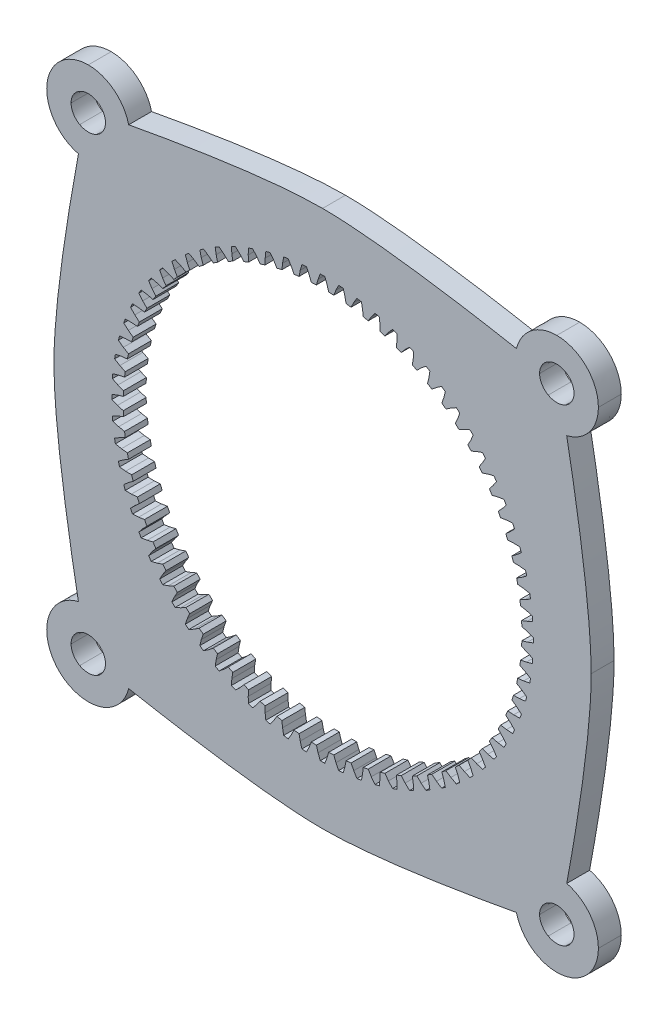
SolidWorks part; units mm, degrees
ref_plane "Front Plane" through (0, 0, 0) normal (0, 0, 1) x (1, 0, 0)
ref_plane "Top Plane" through (0, 0, 0) normal (0, 1, 0) x (1, 0, 0)
ref_plane "Right Plane" through (0, 0, 0) normal (1, 0, 0) x (0, 0, -1)
sketch "ring" plane through (10.9807, 0, 0) normal (0, 0, 1) x (1, 0, 0)
  line L432 (61.0696, 218.6762) -> (61.8666, 218.4468)
  line L433 (61.8666, 218.4468) -> (62.6621, 218.14)
  line L434 (62.6621, 218.14) -> (62.6621, 217.5117)
  line L435 (62.6621, 217.5117) -> (61.8666, 217.205)
  line L436 (61.8666, 217.205) -> (61.0696, 216.9755)
  line L437 (61.0696, 216.9755) -> (61.0385, 216.2626)
  line L438 (61.0385, 216.2626) -> (61.8124, 215.9646)
  line L439 (61.8124, 215.9646) -> (62.578, 215.5895)
  line L440 (62.578, 215.5895) -> (62.5233, 214.9638)
  line L441 (62.5233, 214.9638) -> (61.704, 214.7276)
  line L442 (61.704, 214.7276) -> (60.8904, 214.5682)
  line L443 (60.8904, 214.5682) -> (60.7972, 213.8609)
  line L444 (60.7972, 213.8609) -> (61.542, 213.4966)
  line L445 (61.542, 213.4966) -> (62.2721, 213.0563)
  line L446 (62.2721, 213.0563) -> (62.1632, 212.4377)
  line L447 (62.1632, 212.4377) -> (61.3264, 212.2737)
  line L448 (61.3264, 212.2737) -> (60.5017, 212.1859)
  line L449 (60.5017, 212.1859) -> (60.3474, 211.4894)
  line L450 (60.3474, 211.4894) -> (61.0577, 211.0616)
  line L451 (61.0577, 211.0616) -> (61.7466, 210.5592)
  line L452 (61.7466, 210.5592) -> (61.5841, 209.9524)
  line L453 (61.5841, 209.9524) -> (60.7363, 209.8621)
  line L454 (60.7363, 209.8621) -> (59.9071, 209.8466)
  line L455 (59.9071, 209.8466) -> (59.6926, 209.1662)
  line L456 (59.6926, 209.1662) -> (60.3629, 208.6779)
  line L457 (60.3629, 208.6779) -> (61.0055, 208.1174)
  line L458 (61.0055, 208.1174) -> (60.7907, 207.5273)
  line L459 (60.7907, 207.5273) -> (59.9381, 207.5112)
  line L460 (59.9381, 207.5112) -> (59.1109, 207.5679)
  line L461 (59.1109, 207.5679) -> (58.8378, 206.9087)
  line L462 (58.8378, 206.9087) -> (59.4632, 206.364)
  line L463 (59.4632, 206.364) -> (60.0544, 205.7496)
  line L464 (60.0544, 205.7496) -> (59.7891, 205.1803)
  line L465 (59.7891, 205.1803) -> (58.9382, 205.2385)
  line L466 (58.9382, 205.2385) -> (58.1189, 205.3672)
  line L467 (58.1189, 205.3672) -> (57.7896, 204.7344)
  line L468 (57.7896, 204.7344) -> (58.365, 204.1372)
  line L469 (58.365, 204.1372) -> (58.9007, 203.4737)
  line L470 (58.9007, 203.4737) -> (58.5866, 202.9299)
  line L471 (58.5866, 202.9299) -> (57.7441, 203.062)
  line L472 (57.7441, 203.062) -> (56.9392, 203.2615)
  line L473 (56.9392, 203.2615) -> (56.556, 202.6598)
  line L474 (56.556, 202.6598) -> (57.077, 202.0146)
  line L475 (57.077, 202.0146) -> (57.5528, 201.3068)
  line L476 (57.5528, 201.3068) -> (57.1924, 200.7926)
  line L477 (57.1924, 200.7926) -> (56.3646, 200.9975)
  line L478 (56.3646, 200.9975) -> (55.5803, 201.2665)
  line L479 (55.5803, 201.2665) -> (55.146, 200.7006)
  line L480 (55.146, 200.7006) -> (55.6089, 200.0126)
  line L481 (55.6089, 200.0126) -> (56.0212, 199.2661)
  line L482 (56.0212, 199.2661) -> (55.6173, 198.7849)
  line L483 (55.6173, 198.7849) -> (54.8107, 199.0612)
  line L484 (54.8107, 199.0612) -> (54.0527, 199.3976)
  line L485 (54.0527, 199.3976) -> (53.5706, 198.8715)
  line L486 (53.5706, 198.8715) -> (53.972, 198.1457)
  line L487 (53.972, 198.1457) -> (54.3174, 197.3662)
  line L488 (54.3174, 197.3662) -> (53.8735, 196.9222)
  line L489 (53.8735, 196.9222) -> (53.094, 197.2677)
  line L490 (53.094, 197.2677) -> (52.3681, 197.669)
  line L491 (52.3681, 197.669) -> (51.842, 197.187)
  line L492 (51.842, 197.187) -> (52.1784, 196.4289)
  line L493 (52.1784, 196.4289) -> (52.4547, 195.6223)
  line L494 (52.4547, 195.6223) -> (51.9735, 195.2185)
  line L495 (51.9735, 195.2185) -> (51.2271, 195.6308)
  line L496 (51.2271, 195.6308) -> (50.539, 196.0936)
  line L497 (50.539, 196.0936) -> (49.9732, 195.6593)
  line L498 (49.9732, 195.6593) -> (50.2421, 194.875)
  line L499 (50.2421, 194.875) -> (50.447, 194.0472)
  line L500 (50.447, 194.0472) -> (49.9328, 193.6868)
  line L501 (49.9328, 193.6868) -> (49.225, 194.1627)
  line L502 (49.225, 194.1627) -> (48.5798, 194.6836)
  line L503 (48.5798, 194.6836) -> (47.9781, 194.3004)
  line L504 (47.9781, 194.3004) -> (48.1777, 193.4955)
  line L505 (48.1777, 193.4955) -> (48.3097, 192.6531)
  line L506 (48.3097, 192.6531) -> (47.7659, 192.3389)
  line L507 (47.7659, 192.3389) -> (47.1024, 192.8746)
  line L508 (47.1024, 192.8746) -> (46.5052, 193.45)
  line L509 (46.5052, 193.45) -> (45.8725, 193.1207)
  line L510 (45.8725, 193.1207) -> (46.0012, 192.3014)
  line L511 (46.0012, 192.3014) -> (46.0593, 191.4505)
  line L512 (46.0593, 191.4505) -> (45.4901, 191.1852)
  line L513 (45.4901, 191.1852) -> (44.8757, 191.7765)
  line L514 (44.8757, 191.7765) -> (44.331, 192.4019)
  line L515 (44.331, 192.4019) -> (43.6717, 192.1287)
  line L516 (43.6717, 192.1287) -> (43.7284, 191.3015)
  line L517 (43.7284, 191.3015) -> (43.7123, 190.4489)
  line L518 (43.7123, 190.4489) -> (43.1222, 190.2341)
  line L519 (43.1222, 190.2341) -> (42.5617, 190.8767)
  line L520 (42.5617, 190.8767) -> (42.0735, 191.547)
  line L521 (42.0735, 191.547) -> (41.393, 191.3325)
  line L522 (41.393, 191.3325) -> (41.3775, 190.5034)
  line L523 (41.3775, 190.5034) -> (41.2872, 189.6556)
  line L524 (41.2872, 189.6556) -> (40.6804, 189.493)
  line L525 (40.6804, 189.493) -> (40.1781, 190.1819)
  line L526 (40.1781, 190.1819) -> (39.7502, 190.8923)
  line L527 (39.7502, 190.8923) -> (39.0537, 190.7379)
  line L528 (39.0537, 190.7379) -> (38.9659, 189.9132)
  line L529 (38.9659, 189.9132) -> (38.802, 189.0764)
  line L530 (38.802, 189.0764) -> (38.1833, 188.9675)
  line L531 (38.1833, 188.9675) -> (37.7431, 189.6976)
  line L532 (37.7431, 189.6976) -> (37.3787, 190.4424)
  line L533 (37.3787, 190.4424) -> (36.6715, 190.3493)
  line L534 (36.6715, 190.3493) -> (36.512, 189.5356)
  line L535 (36.512, 189.5356) -> (36.2758, 188.7163)
  line L536 (36.2758, 188.7163) -> (35.6501, 188.6616)
  line L537 (35.6501, 188.6616) -> (35.275, 189.4273)
  line L538 (35.275, 189.4273) -> (34.977, 190.2011)
  line L539 (34.977, 190.2011) -> (34.2641, 190.1701)
  line L540 (34.2641, 190.1701) -> (34.0347, 189.3731)
  line L541 (34.0347, 189.3731) -> (33.7279, 188.5775)
  line L542 (33.7279, 188.5775) -> (33.0997, 188.5775)
  line L543 (33.0997, 188.5775) -> (32.7929, 189.3731)
  line L544 (32.7929, 189.3731) -> (32.5634, 190.1701)
  line L545 (32.5634, 190.1701) -> (31.8505, 190.2011)
  line L546 (31.8505, 190.2011) -> (31.5525, 189.4273)
  line L547 (31.5525, 189.4273) -> (31.1774, 188.6616)
  line L548 (31.1774, 188.6616) -> (30.5518, 188.7163)
  line L549 (30.5518, 188.7163) -> (30.3155, 189.5356)
  line L550 (30.3155, 189.5356) -> (30.1561, 190.3493)
  line L551 (30.1561, 190.3493) -> (29.4488, 190.4424)
  line L552 (29.4488, 190.4424) -> (29.0845, 189.6976)
  line L553 (29.0845, 189.6976) -> (28.6442, 188.9675)
  line L554 (28.6442, 188.9675) -> (28.0256, 189.0764)
  line L555 (28.0256, 189.0764) -> (27.8616, 189.9132)
  line L556 (27.8616, 189.9132) -> (27.7738, 190.7379)
  line L557 (27.7738, 190.7379) -> (27.0773, 190.8923)
  line L558 (27.0773, 190.8923) -> (26.6495, 190.1819)
  line L559 (26.6495, 190.1819) -> (26.1471, 189.493)
  line L560 (26.1471, 189.493) -> (25.5403, 189.6556)
  line L561 (25.5403, 189.6556) -> (25.45, 190.5034)
  line L562 (25.45, 190.5034) -> (25.4345, 191.3325)
  line L563 (25.4345, 191.3325) -> (24.7541, 191.547)
  line L564 (24.7541, 191.547) -> (24.2658, 190.8767)
  line L565 (24.2658, 190.8767) -> (23.7053, 190.2341)
  line L566 (23.7053, 190.2341) -> (23.1152, 190.4489)
  line L567 (23.1152, 190.4489) -> (23.0991, 191.3015)
  line L568 (23.0991, 191.3015) -> (23.1558, 192.1287)
  line L569 (23.1558, 192.1287) -> (22.4966, 192.4019)
  line L570 (22.4966, 192.4019) -> (21.9519, 191.7765)
  line L571 (21.9519, 191.7765) -> (21.3375, 191.1852)
  line L572 (21.3375, 191.1852) -> (20.7682, 191.4505)
  line L573 (20.7682, 191.4505) -> (20.8264, 192.3014)
  line L574 (20.8264, 192.3014) -> (20.9551, 193.1207)
  line L575 (20.9551, 193.1207) -> (20.3223, 193.45)
  line L576 (20.3223, 193.45) -> (19.7251, 192.8746)
  line L577 (19.7251, 192.8746) -> (19.0616, 192.3389)
  line L578 (19.0616, 192.3389) -> (18.5178, 192.6531)
  line L579 (18.5178, 192.6531) -> (18.6499, 193.4955)
  line L580 (18.6499, 193.4955) -> (18.8494, 194.3004)
  line L581 (18.8494, 194.3004) -> (18.2477, 194.6836)
  line L582 (18.2477, 194.6836) -> (17.6025, 194.1627)
  line L583 (17.6025, 194.1627) -> (16.8947, 193.6868)
  line L584 (16.8947, 193.6868) -> (16.3805, 194.0472)
  line L585 (16.3805, 194.0472) -> (16.5854, 194.875)
  line L586 (16.5854, 194.875) -> (16.8544, 195.6593)
  line L587 (16.8544, 195.6593) -> (16.2885, 196.0936)
  line L588 (16.2885, 196.0936) -> (15.6005, 195.6308)
  line L589 (15.6005, 195.6308) -> (14.854, 195.2185)
  line L590 (14.854, 195.2185) -> (14.3728, 195.6223)
  line L591 (14.3728, 195.6223) -> (14.6491, 196.4289)
  line L592 (14.6491, 196.4289) -> (14.9855, 197.187)
  line L593 (14.9855, 197.187) -> (14.4594, 197.669)
  line L594 (14.4594, 197.669) -> (13.7336, 197.2677)
  line L595 (13.7336, 197.2677) -> (12.9541, 196.9222)
  line L596 (12.9541, 196.9222) -> (12.5101, 197.3662)
  line L597 (12.5101, 197.3662) -> (12.8556, 198.1457)
  line L598 (12.8556, 198.1457) -> (13.2569, 198.8715)
  line L599 (13.2569, 198.8715) -> (12.7749, 199.3976)
  line L600 (12.7749, 199.3976) -> (12.0168, 199.0612)
  line L601 (12.0168, 199.0612) -> (11.2102, 198.7849)
  line L602 (11.2102, 198.7849) -> (10.8064, 199.2661)
  line L603 (10.8064, 199.2661) -> (11.2187, 200.0126)
  line L604 (11.2187, 200.0126) -> (11.6815, 200.7006)
  line L605 (11.6815, 200.7006) -> (11.2472, 201.2665)
  line L606 (11.2472, 201.2665) -> (10.4629, 200.9975)
  line L607 (10.4629, 200.9975) -> (9.6351, 200.7926)
  line L608 (9.6351, 200.7926) -> (9.2747, 201.3068)
  line L609 (9.2747, 201.3068) -> (9.7506, 202.0146)
  line L610 (9.7506, 202.0146) -> (10.2715, 202.6598)
  line L611 (10.2715, 202.6598) -> (9.8883, 203.2615)
  line L612 (9.8883, 203.2615) -> (9.0834, 203.062)
  line L613 (9.0834, 203.062) -> (8.241, 202.9299)
  line L614 (8.241, 202.9299) -> (7.9268, 203.4737)
  line L615 (7.9268, 203.4737) -> (8.4625, 204.1372)
  line L616 (8.4625, 204.1372) -> (9.038, 204.7344)
  line L617 (9.038, 204.7344) -> (8.7086, 205.3672)
  line L618 (8.7086, 205.3672) -> (7.8893, 205.2385)
  line L619 (7.8893, 205.2385) -> (7.0384, 205.1803)
  line L620 (7.0384, 205.1803) -> (6.7731, 205.7496)
  line L621 (6.7731, 205.7496) -> (7.3644, 206.364)
  line L622 (7.3644, 206.364) -> (7.9898, 206.9087)
  line L623 (7.9898, 206.9087) -> (7.7166, 207.5679)
  line L624 (7.7166, 207.5679) -> (6.8894, 207.5112)
  line L625 (6.8894, 207.5112) -> (6.0368, 207.5273)
  line L626 (6.0368, 207.5273) -> (5.822, 208.1174)
  line L627 (5.822, 208.1174) -> (6.4646, 208.6779)
  line L628 (6.4646, 208.6779) -> (7.1349, 209.1662)
  line L629 (7.1349, 209.1662) -> (6.9204, 209.8466)
  line L630 (6.9204, 209.8466) -> (6.0913, 209.8621)
  line L631 (6.0913, 209.8621) -> (5.2435, 209.9524)
  line L632 (5.2435, 209.9524) -> (5.0809, 210.5592)
  line L633 (5.0809, 210.5592) -> (5.7698, 211.0616)
  line L634 (5.7698, 211.0616) -> (6.4802, 211.4894)
  line L635 (6.4802, 211.4894) -> (6.3258, 212.1859)
  line L636 (6.3258, 212.1859) -> (5.5011, 212.2737)
  line L637 (5.5011, 212.2737) -> (4.6644, 212.4377)
  line L638 (4.6644, 212.4377) -> (4.5554, 213.0563)
  line L639 (4.5554, 213.0563) -> (5.2855, 213.4966)
  line L640 (5.2855, 213.4966) -> (6.0303, 213.8609)
  line L641 (6.0303, 213.8609) -> (5.9372, 214.5682)
  line L642 (5.9372, 214.5682) -> (5.1235, 214.7276)
  line L643 (5.1235, 214.7276) -> (4.3042, 214.9638)
  line L644 (4.3042, 214.9638) -> (4.2495, 215.5895)
  line L645 (4.2495, 215.5895) -> (5.0152, 215.9646)
  line L646 (5.0152, 215.9646) -> (5.789, 216.2626)
  line L647 (5.789, 216.2626) -> (5.758, 216.9755)
  line L648 (5.758, 216.9755) -> (4.961, 217.205)
  line L649 (4.961, 217.205) -> (4.1654, 217.5117)
  line L650 (4.1654, 217.5117) -> (4.1654, 218.14)
  line L651 (4.1654, 218.14) -> (4.961, 218.4468)
  line L652 (4.961, 218.4468) -> (5.758, 218.6762)
  line L653 (5.758, 218.6762) -> (5.789, 219.3891)
  line L654 (5.789, 219.3891) -> (5.0152, 219.6871)
  line L655 (5.0152, 219.6871) -> (4.2495, 220.0622)
  line L656 (4.2495, 220.0622) -> (4.3042, 220.6879)
  line L657 (4.3042, 220.6879) -> (5.1235, 220.9241)
  line L658 (5.1235, 220.9241) -> (5.9372, 221.0836)
  line L659 (5.9372, 221.0836) -> (6.0303, 221.7908)
  line L660 (6.0303, 221.7908) -> (5.2855, 222.1552)
  line L661 (5.2855, 222.1552) -> (4.5554, 222.5954)
  line L662 (4.5554, 222.5954) -> (4.6644, 223.214)
  line L663 (4.6644, 223.214) -> (5.5011, 223.378)
  line L664 (5.5011, 223.378) -> (6.3258, 223.4658)
  line L665 (6.3258, 223.4658) -> (6.4802, 224.1623)
  line L666 (6.4802, 224.1623) -> (5.7698, 224.5902)
  line L667 (5.7698, 224.5902) -> (5.0809, 225.0925)
  line L668 (5.0809, 225.0925) -> (5.2435, 225.6993)
  line L669 (5.2435, 225.6993) -> (6.0913, 225.7896)
  line L670 (6.0913, 225.7896) -> (6.9204, 225.8051)
  line L671 (6.9204, 225.8051) -> (7.1349, 226.4856)
  line L672 (7.1349, 226.4856) -> (6.4646, 226.9738)
  line L673 (6.4646, 226.9738) -> (5.822, 227.5343)
  line L674 (5.822, 227.5343) -> (6.0368, 228.1244)
  line L675 (6.0368, 228.1244) -> (6.8894, 228.1405)
  line L676 (6.8894, 228.1405) -> (7.7166, 228.0838)
  line L677 (7.7166, 228.0838) -> (7.9898, 228.7431)
  line L678 (7.9898, 228.7431) -> (7.3644, 229.2878)
  line L679 (7.3644, 229.2878) -> (6.7731, 229.9022)
  line L680 (6.7731, 229.9022) -> (7.0384, 230.4714)
  line L681 (7.0384, 230.4714) -> (7.8893, 230.4133)
  line L682 (7.8893, 230.4133) -> (8.7086, 230.2846)
  line L683 (8.7086, 230.2846) -> (9.038, 230.9173)
  line L684 (9.038, 230.9173) -> (8.4625, 231.5145)
  line L685 (8.4625, 231.5145) -> (7.9268, 232.178)
  line L686 (7.9268, 232.178) -> (8.241, 232.7218)
  line L687 (8.241, 232.7218) -> (9.0834, 232.5898)
  line L688 (9.0834, 232.5898) -> (9.8883, 232.3902)
  line L689 (9.8883, 232.3902) -> (10.2715, 232.9919)
  line L690 (10.2715, 232.9919) -> (9.7506, 233.6371)
  line L691 (9.7506, 233.6371) -> (9.2747, 234.3449)
  line L692 (9.2747, 234.3449) -> (9.6351, 234.8591)
  line L693 (9.6351, 234.8591) -> (10.4629, 234.6542)
  line L694 (10.4629, 234.6542) -> (11.2472, 234.3853)
  line L695 (11.2472, 234.3853) -> (11.6815, 234.9511)
  line L696 (11.6815, 234.9511) -> (11.2187, 235.6392)
  line L697 (11.2187, 235.6392) -> (10.8064, 236.3856)
  line L698 (10.8064, 236.3856) -> (11.2102, 236.8668)
  line L699 (11.2102, 236.8668) -> (12.0168, 236.5905)
  line L700 (12.0168, 236.5905) -> (12.7749, 236.2541)
  line L701 (12.7749, 236.2541) -> (13.2569, 236.7802)
  line L702 (13.2569, 236.7802) -> (12.8556, 237.5061)
  line L703 (12.8556, 237.5061) -> (12.5101, 238.2856)
  line L704 (12.5101, 238.2856) -> (12.9541, 238.7295)
  line L705 (12.9541, 238.7295) -> (13.7336, 238.3841)
  line L706 (13.7336, 238.3841) -> (14.4594, 237.9827)
  line L707 (14.4594, 237.9827) -> (14.9855, 238.4648)
  line L708 (14.9855, 238.4648) -> (14.6491, 239.2228)
  line L709 (14.6491, 239.2228) -> (14.3728, 240.0294)
  line L710 (14.3728, 240.0294) -> (14.854, 240.4333)
  line L711 (14.854, 240.4333) -> (15.6005, 240.0209)
  line L712 (15.6005, 240.0209) -> (16.2885, 239.5581)
  line L713 (16.2885, 239.5581) -> (16.8544, 239.9924)
  line L714 (16.8544, 239.9924) -> (16.5854, 240.7767)
  line L715 (16.5854, 240.7767) -> (16.3805, 241.6045)
  line L716 (16.3805, 241.6045) -> (16.8947, 241.9649)
  line L717 (16.8947, 241.9649) -> (17.6025, 241.4891)
  line L718 (17.6025, 241.4891) -> (18.2477, 240.9681)
  line L719 (18.2477, 240.9681) -> (18.8494, 241.3513)
  line L720 (18.8494, 241.3513) -> (18.6499, 242.1562)
  line L721 (18.6499, 242.1562) -> (18.5178, 242.9987)
  line L722 (18.5178, 242.9987) -> (19.0616, 243.3128)
  line L723 (19.0616, 243.3128) -> (19.7251, 242.7771)
  line L724 (19.7251, 242.7771) -> (20.3223, 242.2017)
  line L725 (20.3223, 242.2017) -> (20.9551, 242.531)
  line L726 (20.9551, 242.531) -> (20.8264, 243.3503)
  line L727 (20.8264, 243.3503) -> (20.7682, 244.2012)
  line L728 (20.7682, 244.2012) -> (21.3375, 244.4665)
  line L729 (21.3375, 244.4665) -> (21.9519, 243.8753)
  line L730 (21.9519, 243.8753) -> (22.4966, 243.2499)
  line L731 (22.4966, 243.2499) -> (23.1558, 243.523)
  line L732 (23.1558, 243.523) -> (23.0991, 244.3502)
  line L733 (23.0991, 244.3502) -> (23.1152, 245.2028)
  line L734 (23.1152, 245.2028) -> (23.7053, 245.4176)
  line L735 (23.7053, 245.4176) -> (24.2658, 244.775)
  line L736 (24.2658, 244.775) -> (24.7541, 244.1047)
  line L737 (24.7541, 244.1047) -> (25.4345, 244.3192)
  line L738 (25.4345, 244.3192) -> (25.45, 245.1484)
  line L739 (25.45, 245.1484) -> (25.5403, 245.9962)
  line L740 (25.5403, 245.9962) -> (26.1471, 246.1587)
  line L741 (26.1471, 246.1587) -> (26.6495, 245.4698)
  line L742 (26.6495, 245.4698) -> (27.0773, 244.7595)
  line L743 (27.0773, 244.7595) -> (27.7738, 244.9138)
  line L744 (27.7738, 244.9138) -> (27.8616, 245.7385)
  line L745 (27.8616, 245.7385) -> (28.0256, 246.5753)
  line L746 (28.0256, 246.5753) -> (28.6442, 246.6842)
  line L747 (28.6442, 246.6842) -> (29.0845, 245.9541)
  line L748 (29.0845, 245.9541) -> (29.4488, 245.2093)
  line L749 (29.4488, 245.2093) -> (30.1561, 245.3025)
  line L750 (30.1561, 245.3025) -> (30.3155, 246.1161)
  line L751 (30.3155, 246.1161) -> (30.5518, 246.9354)
  line L752 (30.5518, 246.9354) -> (31.1774, 246.9901)
  line L753 (31.1774, 246.9901) -> (31.5525, 246.2245)
  line L754 (31.5525, 246.2245) -> (31.8505, 245.4506)
  line L755 (31.8505, 245.4506) -> (32.5634, 245.4817)
  line L756 (32.5634, 245.4817) -> (32.7929, 246.2787)
  line L757 (32.7929, 246.2787) -> (33.0997, 247.0742)
  line L758 (33.0997, 247.0742) -> (33.7279, 247.0742)
  line L759 (33.7279, 247.0742) -> (34.0347, 246.2787)
  line L760 (34.0347, 246.2787) -> (34.2641, 245.4817)
  line L761 (34.2641, 245.4817) -> (34.977, 245.4506)
  line L762 (34.977, 245.4506) -> (35.275, 246.2245)
  line L763 (35.275, 246.2245) -> (35.6501, 246.9901)
  line L764 (35.6501, 246.9901) -> (36.2758, 246.9354)
  line L765 (36.2758, 246.9354) -> (36.512, 246.1161)
  line L766 (36.512, 246.1161) -> (36.6715, 245.3025)
  line L767 (36.6715, 245.3025) -> (37.3787, 245.2093)
  line L768 (37.3787, 245.2093) -> (37.7431, 245.9541)
  line L769 (37.7431, 245.9541) -> (38.1833, 246.6842)
  line L770 (38.1833, 246.6842) -> (38.802, 246.5753)
  line L771 (38.802, 246.5753) -> (38.9659, 245.7385)
  line L772 (38.9659, 245.7385) -> (39.0537, 244.9138)
  line L773 (39.0537, 244.9138) -> (39.7502, 244.7595)
  line L774 (39.7502, 244.7595) -> (40.1781, 245.4698)
  line L775 (40.1781, 245.4698) -> (40.6804, 246.1587)
  line L776 (40.6804, 246.1587) -> (41.2872, 245.9962)
  line L777 (41.2872, 245.9962) -> (41.3775, 245.1484)
  line L778 (41.3775, 245.1484) -> (41.393, 244.3192)
  line L779 (41.393, 244.3192) -> (42.0735, 244.1047)
  line L780 (42.0735, 244.1047) -> (42.5617, 244.775)
  line L781 (42.5617, 244.775) -> (43.1222, 245.4176)
  line L782 (43.1222, 245.4176) -> (43.7123, 245.2028)
  line L783 (43.7123, 245.2028) -> (43.7284, 244.3502)
  line L784 (43.7284, 244.3502) -> (43.6717, 243.523)
  line L785 (43.6717, 243.523) -> (44.331, 243.2499)
  line L786 (44.331, 243.2499) -> (44.8757, 243.8753)
  line L787 (44.8757, 243.8753) -> (45.4901, 244.4665)
  line L788 (45.4901, 244.4665) -> (46.0593, 244.2012)
  line L789 (46.0593, 244.2012) -> (46.0012, 243.3503)
  line L790 (46.0012, 243.3503) -> (45.8725, 242.531)
  line L791 (45.8725, 242.531) -> (46.5052, 242.2017)
  line L792 (46.5052, 242.2017) -> (47.1024, 242.7771)
  line L793 (47.1024, 242.7771) -> (47.7659, 243.3128)
  line L794 (47.7659, 243.3128) -> (48.3097, 242.9987)
  line L795 (48.3097, 242.9987) -> (48.1777, 242.1562)
  line L796 (48.1777, 242.1562) -> (47.9781, 241.3513)
  line L797 (47.9781, 241.3513) -> (48.5798, 240.9681)
  line L798 (48.5798, 240.9681) -> (49.225, 241.4891)
  line L799 (49.225, 241.4891) -> (49.9328, 241.9649)
  line L800 (49.9328, 241.9649) -> (50.447, 241.6045)
  line L801 (50.447, 241.6045) -> (50.2421, 240.7767)
  line L802 (50.2421, 240.7767) -> (49.9732, 239.9924)
  line L803 (49.9732, 239.9924) -> (50.539, 239.5581)
  line L804 (50.539, 239.5581) -> (51.2271, 240.0209)
  line L805 (51.2271, 240.0209) -> (51.9735, 240.4333)
  line L806 (51.9735, 240.4333) -> (52.4547, 240.0294)
  line L807 (52.4547, 240.0294) -> (52.1784, 239.2228)
  line L808 (52.1784, 239.2228) -> (51.842, 238.4648)
  line L809 (51.842, 238.4648) -> (52.3681, 237.9827)
  line L810 (52.3681, 237.9827) -> (53.094, 238.3841)
  line L811 (53.094, 238.3841) -> (53.8735, 238.7295)
  line L812 (53.8735, 238.7295) -> (54.3174, 238.2856)
  line L813 (54.3174, 238.2856) -> (53.972, 237.5061)
  line L814 (53.972, 237.5061) -> (53.5706, 236.7802)
  line L815 (53.5706, 236.7802) -> (54.0527, 236.2541)
  line L816 (54.0527, 236.2541) -> (54.8107, 236.5905)
  line L817 (54.8107, 236.5905) -> (55.6173, 236.8668)
  line L818 (55.6173, 236.8668) -> (56.0212, 236.3856)
  line L819 (56.0212, 236.3856) -> (55.6089, 235.6392)
  line L820 (55.6089, 235.6392) -> (55.146, 234.9511)
  line L821 (55.146, 234.9511) -> (55.5803, 234.3853)
  line L822 (55.5803, 234.3853) -> (56.3646, 234.6542)
  line L823 (56.3646, 234.6542) -> (57.1924, 234.8591)
  line L824 (57.1924, 234.8591) -> (57.5528, 234.3449)
  line L825 (57.5528, 234.3449) -> (57.077, 233.6371)
  line L826 (57.077, 233.6371) -> (56.556, 232.9919)
  line L827 (56.556, 232.9919) -> (56.9392, 232.3902)
  line L828 (56.9392, 232.3902) -> (57.7441, 232.5898)
  line L829 (57.7441, 232.5898) -> (58.5866, 232.7218)
  line L830 (58.5866, 232.7218) -> (58.9007, 232.178)
  line L831 (58.9007, 232.178) -> (58.365, 231.5145)
  line L832 (58.365, 231.5145) -> (57.7896, 230.9173)
  line L833 (57.7896, 230.9173) -> (58.1189, 230.2846)
  line L834 (58.1189, 230.2846) -> (58.9382, 230.4133)
  line L835 (58.9382, 230.4133) -> (59.7891, 230.4714)
  line L836 (59.7891, 230.4714) -> (60.0544, 229.9022)
  line L837 (60.0544, 229.9022) -> (59.4632, 229.2878)
  line L838 (59.4632, 229.2878) -> (58.8378, 228.7431)
  line L839 (58.8378, 228.7431) -> (59.1109, 228.0838)
  line L840 (59.1109, 228.0838) -> (59.9381, 228.1405)
  line L841 (59.9381, 228.1405) -> (60.7907, 228.1244)
  line L842 (60.7907, 228.1244) -> (61.0055, 227.5343)
  line L843 (61.0055, 227.5343) -> (60.3629, 226.9738)
  line L844 (60.3629, 226.9738) -> (59.6926, 226.4856)
  line L845 (59.6926, 226.4856) -> (59.9071, 225.8051)
  line L846 (59.9071, 225.8051) -> (60.7363, 225.7896)
  line L847 (60.7363, 225.7896) -> (61.5841, 225.6993)
  line L848 (61.5841, 225.6993) -> (61.7466, 225.0925)
  line L849 (61.7466, 225.0925) -> (61.0577, 224.5902)
  line L850 (61.0577, 224.5902) -> (60.3474, 224.1623)
  line L851 (60.3474, 224.1623) -> (60.5017, 223.4658)
  line L852 (60.5017, 223.4658) -> (61.3264, 223.378)
  line L853 (61.3264, 223.378) -> (62.1632, 223.214)
  line L854 (62.1632, 223.214) -> (62.2721, 222.5954)
  line L855 (62.2721, 222.5954) -> (61.542, 222.1552)
  line L856 (61.542, 222.1552) -> (60.7972, 221.7908)
  line L857 (60.7972, 221.7908) -> (60.8904, 221.0836)
  line L858 (60.8904, 221.0836) -> (61.704, 220.9241)
  line L859 (61.704, 220.9241) -> (62.5233, 220.6879)
  line L860 (62.5233, 220.6879) -> (62.578, 220.0622)
  line L861 (62.578, 220.0622) -> (61.8124, 219.6871)
  line L862 (61.8124, 219.6871) -> (61.0385, 219.3891)
  line L863 (61.0385, 219.3891) -> (61.0696, 218.6762)
  spline S44 degree 3 poles (0.9066, 256.1037) (-2.2787, 256.1037) (-4.8614, 253.521) (-4.8614, 250.3358) knots 0 0 0 0 1 1 1 1
  spline S45 degree 3 poles (-4.8614, 250.3358) (-4.8614, 247.6204) (-2.9874, 245.3481) (-0.4605, 244.7354) knots 0 0 0 0 1 1 1 1
  spline S46 degree 3 poles (-0.4605, 244.7354) (-1.8035, 237.5255) (-3.8648, 225.2891) (-3.8648, 217.8273) knots 0 0 0 0 1 1 1 1
  spline S47 degree 3 poles (-3.8648, 217.8273) (-3.8648, 210.3691) (-1.8115, 198.1313) (-0.4693, 190.9192) knots 0 0 0 0 1 1 1 1
  spline S48 degree 3 poles (-0.4693, 190.9192) (-2.9923, 190.3037) (-4.8614, 188.0314) (-4.8614, 185.3188) knots 0 0 0 0 1 1 1 1
  spline S49 degree 3 poles (-4.8614, 185.3188) (-4.8614, 182.1336) (-2.2787, 179.5509) (0.9066, 179.5509) knots 0 0 0 0 1 1 1 1
  spline S50 degree 3 poles (0.9066, 179.5509) (3.6191, 179.5509) (5.8914, 181.4199) (6.5069, 183.943) knots 0 0 0 0 1 1 1 1
  spline S51 degree 3 poles (6.5069, 183.943) (13.719, 182.6008) (25.9568, 180.5475) (33.415, 180.5475) knots 0 0 0 0 1 1 1 1
  spline S52 degree 3 poles (33.415, 180.5475) (40.8732, 180.5475) (53.1111, 182.6008) (60.3232, 183.943) knots 0 0 0 0 1 1 1 1
  spline S53 degree 3 poles (60.3232, 183.943) (60.9388, 181.4202) (63.2111, 179.5509) (65.9235, 179.5509) knots 0 0 0 0 1 1 1 1
  spline S54 degree 3 poles (65.9235, 179.5509) (69.1087, 179.5509) (71.6914, 182.1336) (71.6914, 185.3188) knots 0 0 0 0 1 1 1 1
  spline S55 degree 3 poles (71.6914, 185.3188) (71.6914, 188.0291) (69.8192, 190.3014) (67.2993, 190.9192) knots 0 0 0 0 1 1 1 1
  spline S56 degree 3 poles (67.2993, 190.9192) (68.6416, 198.1313) (70.6948, 210.3691) (70.6948, 217.8273) knots 0 0 0 0 1 1 1 1
  spline S57 degree 3 poles (70.6948, 217.8273) (70.6948, 225.2855) (68.6416, 237.5233) (67.2993, 244.7354) knots 0 0 0 0 1 1 1 1
  spline S58 degree 3 poles (67.2993, 244.7354) (69.819, 245.3533) (71.6914, 247.6256) (71.6914, 250.3358) knots 0 0 0 0 1 1 1 1
  spline S59 degree 3 poles (71.6914, 250.3358) (71.6914, 253.521) (69.1087, 256.1037) (65.9235, 256.1037) knots 0 0 0 0 1 1 1 1
  spline S60 degree 3 poles (65.9235, 256.1037) (63.2133, 256.1037) (60.9411, 254.2312) (60.3232, 251.7116) knots 0 0 0 0 1 1 1 1
  spline S61 degree 3 poles (60.3232, 251.7116) (53.1111, 253.0538) (40.8732, 255.1071) (33.415, 255.1071) knots 0 0 0 0 1 1 1 1
  spline S62 degree 3 poles (33.415, 255.1071) (25.9553, 255.1071) (13.7177, 253.0459) (6.5069, 251.7028) knots 0 0 0 0 1 1 1 1
  spline S63 degree 3 poles (6.5069, 251.7028) (5.8922, 254.2269) (3.6199, 256.1037) (0.9066, 256.1037) knots 0 0 0 0 1 1 1 1
  spline S64 degree 3 poles (3.2903, 250.3351) (3.2903, 249.5103) (2.8356, 248.7481) (2.0974, 248.3357) knots 0 0 0 0 1 1 1 1
  spline S65 degree 3 poles (2.0974, 248.3357) (1.3592, 247.9233) (0.4498, 247.9233) (-0.2884, 248.3357) knots 0 0 0 0 1 1 1 1
  spline S66 degree 3 poles (-0.2884, 248.3357) (-1.0266, 248.7481) (-1.4813, 249.5103) (-1.4813, 250.3351) knots 0 0 0 0 1 1 1 1
  spline S67 degree 3 poles (-1.4813, 250.3351) (-1.4813, 251.16) (-1.0266, 251.9221) (-0.2884, 252.3346) knots 0 0 0 0 1 1 1 1
  spline S68 degree 3 poles (-0.2884, 252.3346) (0.4498, 252.747) (1.3592, 252.747) (2.0974, 252.3346) knots 0 0 0 0 1 1 1 1
  spline S69 degree 3 poles (2.0974, 252.3346) (2.8356, 251.9221) (3.2903, 251.16) (3.2903, 250.3351) knots 0 0 0 0 1 1 1 1
  spline S70 degree 3 poles (68.3088, 185.3166) (68.3088, 184.4918) (67.8541, 183.7296) (67.1159, 183.3172) knots 0 0 0 0 1 1 1 1
  spline S71 degree 3 poles (67.1159, 183.3172) (66.3778, 182.9048) (65.4683, 182.9048) (64.7301, 183.3172) knots 0 0 0 0 1 1 1 1
  spline S72 degree 3 poles (64.7301, 183.3172) (63.992, 183.7296) (63.5372, 184.4918) (63.5372, 185.3166) knots 0 0 0 0 1 1 1 1
  spline S73 degree 3 poles (63.5372, 185.3166) (63.5372, 186.1414) (63.992, 186.9036) (64.7301, 187.316) knots 0 0 0 0 1 1 1 1
  spline S74 degree 3 poles (64.7301, 187.316) (65.4683, 187.7285) (66.3778, 187.7285) (67.1159, 187.316) knots 0 0 0 0 1 1 1 1
  spline S75 degree 3 poles (67.1159, 187.316) (67.8541, 186.9036) (68.3088, 186.1414) (68.3088, 185.3166) knots 0 0 0 0 1 1 1 1
  spline S76 degree 3 poles (3.2903, 185.3166) (3.2903, 184.4918) (2.8356, 183.7296) (2.0974, 183.3172) knots 0 0 0 0 1 1 1 1
  spline S77 degree 3 poles (2.0974, 183.3172) (1.3592, 182.9048) (0.4498, 182.9048) (-0.2884, 183.3172) knots 0 0 0 0 1 1 1 1
  spline S78 degree 3 poles (-0.2884, 183.3172) (-1.0266, 183.7296) (-1.4813, 184.4918) (-1.4813, 185.3166) knots 0 0 0 0 1 1 1 1
  spline S79 degree 3 poles (-1.4813, 185.3166) (-1.4813, 186.1414) (-1.0266, 186.9036) (-0.2884, 187.316) knots 0 0 0 0 1 1 1 1
  spline S80 degree 3 poles (-0.2884, 187.316) (0.4498, 187.7285) (1.3592, 187.7285) (2.0974, 187.316) knots 0 0 0 0 1 1 1 1
  spline S81 degree 3 poles (2.0974, 187.316) (2.8356, 186.9036) (3.2903, 186.1414) (3.2903, 185.3166) knots 0 0 0 0 1 1 1 1
  spline S82 degree 3 poles (68.3088, 250.3351) (68.3088, 249.5103) (67.8541, 248.7481) (67.1159, 248.3357) knots 0 0 0 0 1 1 1 1
  spline S83 degree 3 poles (67.1159, 248.3357) (66.3778, 247.9233) (65.4683, 247.9233) (64.7301, 248.3357) knots 0 0 0 0 1 1 1 1
  spline S84 degree 3 poles (64.7301, 248.3357) (63.992, 248.7481) (63.5372, 249.5103) (63.5372, 250.3351) knots 0 0 0 0 1 1 1 1
  spline S85 degree 3 poles (63.5372, 250.3351) (63.5372, 251.16) (63.992, 251.9221) (64.7301, 252.3346) knots 0 0 0 0 1 1 1 1
  spline S86 degree 3 poles (64.7301, 252.3346) (65.4683, 252.747) (66.3778, 252.747) (67.1159, 252.3346) knots 0 0 0 0 1 1 1 1
  spline S87 degree 3 poles (67.1159, 252.3346) (67.8541, 251.9221) (68.3088, 251.16) (68.3088, 250.3351) knots 0 0 0 0 1 1 1 1
extrude "Boss-Extrude1" add sketch "ring" along normal blind 3.175 contours L863 L862 L861 L860 L859 L858 L857 L856 L855 L854 L853 L852 L851 L850 L849 L848 L847 L846 L845 L844 L843 L842 L841 L840 L839 L838 L837 L836 L835 L834 L833 L832 L831 L830 L829 L828 L827 L826 L825 L824 L823 L822 L821 L820 L819 L818 L817 L816 L815 L814 L813 | S81 S80 S79 S78 S77 S76 | S69 S68 S67 S66 S65 S64 | S87 S86 S85 S84 S83 S82 | S75 S74 S73 S72 S71 S70 | S51 S52 S53 S54 S55 S56 S57 S58 S59 S60 S61 S62 S63 S44 S45 S46 S47 S48 S49 S50
